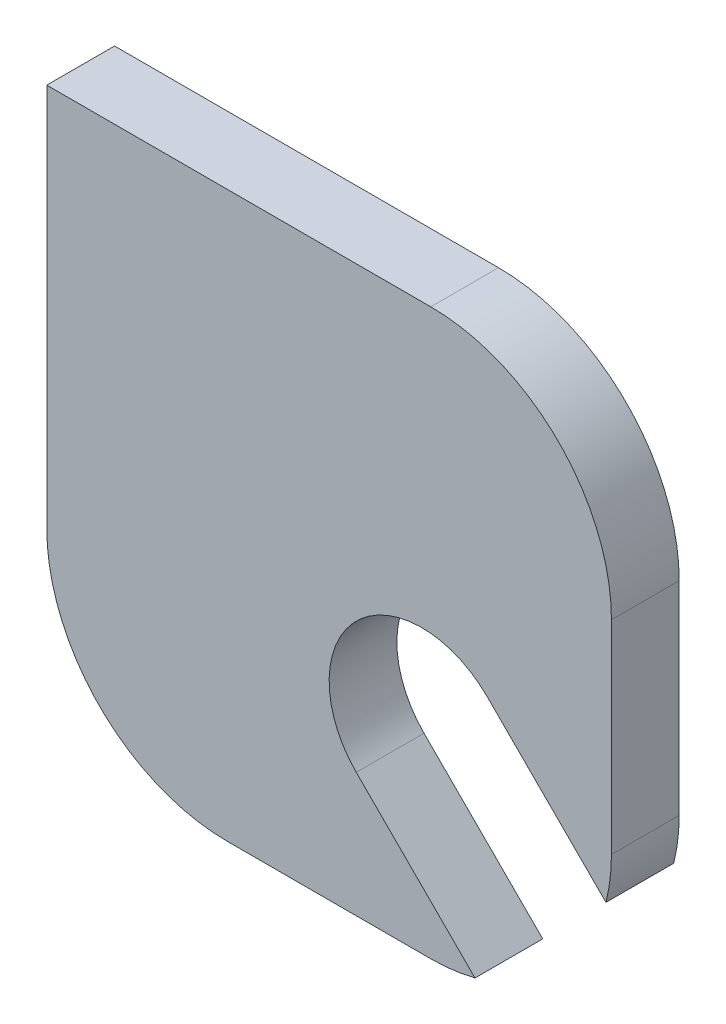
SolidWorks part; units mm, degrees
ref_plane "前视基准面" through (0, 0, 0) normal (0, 0, 1) x (1, 0, 0)
ref_plane "上视基准面" through (0, 0, 0) normal (0, 1, 0) x (1, 0, 0)
ref_plane "右视基准面" through (0, 0, 0) normal (1, 0, 0) x (0, 0, -1)
sketch "草图1" plane through (0, 0, 0) normal (0, 0, 1) x (1, 0, 0)
  line L1 (-12.5, 12.5) -> (12.5, 12.5)
  line L2 (-12.5, 12.5) -> (-12.5, -12.5)
  line L3 (-12.5, -12.5) -> (12.5, -12.5)
  line L4 (12.5, 12.5) -> (12.5, -12.5)
  line L5 (-12.5, 12.5) -> (12.5, -12.5) construction
  line L6 (-12.5, -12.5) -> (12.5, 12.5) construction
  point P0 (0, 0)
  dimension "D1" = 25
  dimension "D2" = 25
extrude "凸台-拉伸1" add sketch "草图1" along normal blind 3
sketch "草图2" plane through (0, 0, 3) normal (0, 0, 1) x (1, 0, 0)
  line L0 (0, 11.9824) -> (0, -13.4177) construction
  line L1 (-15.9657, 0) -> (17.6094, 0) construction
  circle A0 centre (4.1, -4.1) radius 4.1
  point P7 (0, 0)
  point P8 (5.1107, -5.2122)
  point P9 (0, 0)
  dimension "D1" = 8.2
fillet "圆角1" radius 8 1 edges at (-12.5, -12.5, 1.5)
fillet "圆角2" radius 8 1 edges at (12.5, -12.5, 1.5)
fillet "圆角3" radius 8 1 edges at (12.5, 12.5, 1.5)
extrude "切除-拉伸1" cut sketch "草图2" against normal blind 3 contours A0
sketch "草图3" plane through (0, 0, 3) normal (0, 0, 1) x (1, 0, 0)
  line L0 (12.2566, -6.4583) -> (6.9991, -1.2009)
  line L2 (-4.5, -12.5) -> (4.5, -12.5) construction
  line L3 (1.2009, -6.9991) -> (6.4583, -12.2566)
  circle A0 centre (4.1, -4.1) radius 4.1 construction
  arc A2 (4.5, -12.5) -> (12.5, -4.5) centre (4.5, -4.5) ccw construction
  arc A3 (6.9991, -1.2009) -> (1.2009, -6.9991) centre (4.1, -4.1) cw
  arc A4 (12.2566, -6.4583) -> (6.4583, -12.2566) centre (4.5, -4.5) cw
  point P12 (0, 0)
  dimension "D2" = 8
  dimension "D1" = 45
extrude "切除-拉伸2" cut sketch "草图3" against normal blind 3
